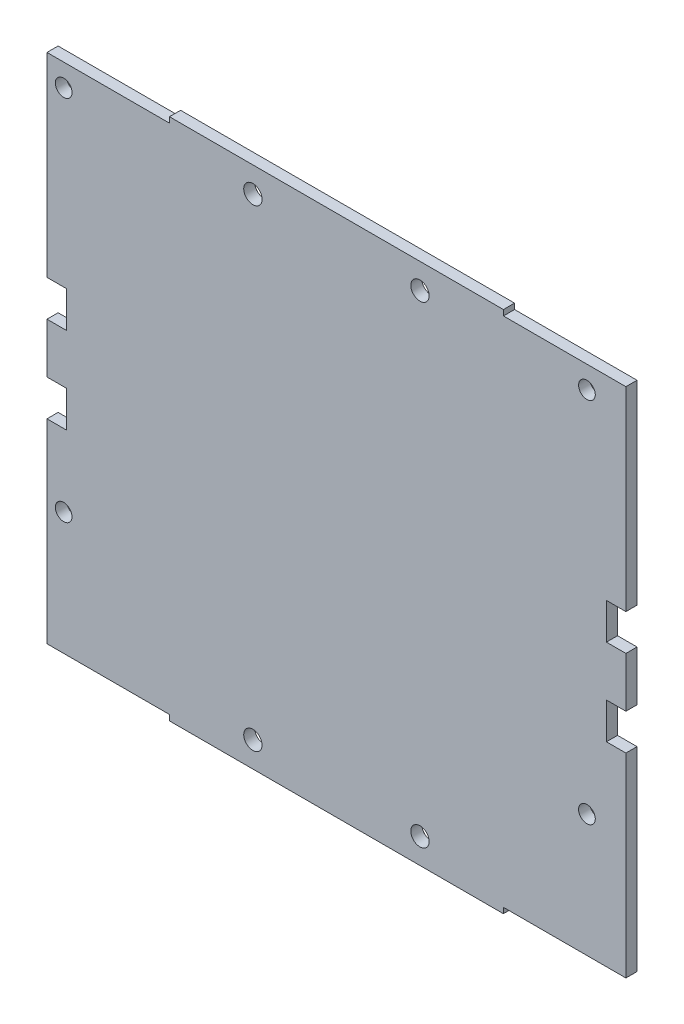
SolidWorks part; units mm, degrees
ref_plane "Front Plane" through (0, 0, 0) normal (0, 0, 1) x (1, 0, 0)
ref_plane "Top Plane" through (0, 0, 0) normal (0, 1, 0) x (1, 0, 0)
ref_plane "Right Plane" through (0, 0, 0) normal (1, 0, 0) x (0, 0, -1)
sketch "Sketch1" plane through (0, 0, 0) normal (0, 0, 1) x (1, 0, 0)
  line L1 (-53, -47.5) -> (53, -47.5)
  line L2 (-53, -47.5) -> (-53, 47.5)
  line L3 (-53, 47.5) -> (53, 47.5)
  line L4 (53, -47.5) -> (53, 47.5)
  line L5 (-53, -47.5) -> (53, 47.5) construction
  line L6 (-53, 47.5) -> (53, -47.5) construction
  line L7 (10.9414, 37.5603) -> (18.9351, 37.5603) construction
  line L8 (10.9414, 37.5603) -> (10.9414, 47.5654) construction
  line L9 (10.9414, 47.5654) -> (18.9351, 47.5654) construction
  line L10 (18.9351, 37.5603) -> (18.9351, 47.5654) construction
  line L11 (10.9414, 37.5603) -> (18.9351, 47.5654) construction
  line L12 (10.9414, 47.5654) -> (18.9351, 37.5603) construction
  line L13 (-19.0649, 47.5415) -> (-11.0586, 47.5415) construction
  line L14 (-19.0649, 47.5415) -> (-19.0649, 37.5465) construction
  line L15 (-19.0649, 37.5465) -> (-11.0586, 37.5465) construction
  line L16 (-11.0586, 47.5415) -> (-11.0586, 37.5465) construction
  line L17 (-19.0649, 47.5415) -> (-11.0586, 37.5465) construction
  line L18 (-19.0649, 37.5465) -> (-11.0586, 47.5415) construction
  point P0 (0, 0)
  point P6 (14.9383, 42.5629)
  point P7 (-15.0617, 42.544)
  dimension "D1" = 95
  dimension "D2" = 106
extrude "Boss-Extrude1" add sketch "Sketch1" along normal blind 2
hole_wizard "Tap Drill for M4x0.7 Tap1" positions "Sketch2" profile "Sketch3" hole size "M4x0.7" standard "ANSI Metric"
sketch "Sketch2" plane through (0, 0, 0) normal (0, 0, -1) x (-1, 0, 0)
  line L1 (-1000, 0) -> (49000, 0) construction
  line L2 (0, -1000) -> (0, 49000) construction
  line L3 (-53, -47.5) -> (-53, 47.5) construction
  line L4 (53, -47.5) -> (-53, -47.5) construction
  line L5 (-53, -47.5) -> (-53, 47.5) construction
  line L6 (53, -47.5) -> (-53, -47.5) construction
  line L8 (-53, -39.5) -> (-45, -39.5)
  line L9 (-53, -39.5) -> (-53, -47.5)
  line L10 (-53, -47.5) -> (-45, -47.5)
  line L11 (-45, -39.5) -> (-45, -47.5)
  line L12 (-53, -39.5) -> (-45, -47.5) construction
  line L13 (-53, -47.5) -> (-45, -39.5) construction
  point P20 (-49, -43.5)
  point P67 (49, -43.5)
  point P70 (-49, 43.5)
  point P72 (49, 43.5)
  dimension "D1" = 8
  dimension "D2" = 8
sketch "Sketch3" plane through (-49, 43.5, 0) normal (1, 0, 0) x (0, 1, 0)
  line L0 (0, 0) -> (0, 10.9914)
  line L1 (0, 10.9914) -> (1.65, 10)
  line L2 (1.65, 10) -> (1.65, 0.025)
  line L3 (1.65, 0.025) -> (1.675, 0)
  line L5 (1.675, 0) -> (0, 0)
  line L6 (-1.65, 0.025) -> (-1.675, 0) construction
  line L10 (0, 10.9914) -> (-1.65, 10) construction
  line L11 (0, -6.35) -> (0, 107.95) construction
  dimension "Hole Dia." = 3.3
  dimension "Hole Depth" = 10
  dimension "Near C'Sink Dia." = 3.35
  dimension "Near C'Sink Angle" = 90
  dimension "Drill Angle" = 118
sketch "Sketch4" plane through (0, 0, 0) normal (0, 0, -1) x (-1, 0, 0)
  line L0 (53, 47.5) -> (53, -47.5) construction
  line L1 (-52, 47) -> (52, 47)
  line L2 (-52, 47) -> (-52, -47)
  line L3 (-52, -47) -> (52, -47)
  line L4 (52, 47) -> (52, -47)
  line L5 (-52, 47) -> (52, -47) construction
  line L6 (-52, -47) -> (52, 47) construction
  line L7 (53, -47.5) -> (-53, -47.5) construction
  line L8 (-53, 47.5) -> (53, 47.5) construction
  line L9 (-64.139, -55.2308) -> (64.139, -55.2308)
  line L10 (-64.139, -55.2308) -> (-64.139, 55.2308)
  line L11 (-64.139, 55.2308) -> (64.139, 55.2308)
  line L12 (64.139, -55.2308) -> (64.139, 55.2308)
  line L13 (-64.139, -55.2308) -> (64.139, 55.2308) construction
  line L14 (-64.139, 55.2308) -> (64.139, -55.2308) construction
  point P0 (0, 0)
  point P9 (0, 0)
  dimension "D1" = 1
  dimension "D2" = 104
  dimension "D3" = 0.5
  dimension "D4" = 0.5
extrude "Cut-Extrude1" cut sketch "Sketch4" against normal blind 10
sketch "Sketch6" plane through (0, 0, 0) normal (0, 0, -1) x (-1, 0, 0)
  line L0 (-52, 47) -> (-52, -47) construction
  line L1 (-52, 47) -> (-52, -47) construction
  line L2 (52, -47) -> (52, 47) construction
  line L3 (52, -47) -> (52, 47) construction
  line L4 (-1000, 0) -> (49000, 0) construction
  line L5 (52, 47) -> (-52, 47) construction
  line L6 (-52, -4.5) -> (-48.5, -4.5)
  line L7 (-52, -4.5) -> (-52, -11)
  line L8 (-52, -11) -> (-48.5, -11)
  line L9 (-48.5, -4.5) -> (-48.5, -11)
  line L10 (-52, -47) -> (52, -47) construction
  line L11 (52, 47) -> (-52, 47) construction
  line L12 (-52, -47) -> (52, -47) construction
  line L13 (-52, 11) -> (-48.5, 11)
  line L14 (-48.5, 4.5) -> (-48.5, 11)
  line L15 (-52, 4.5) -> (-48.5, 4.5)
  line L16 (-52, 4.5) -> (-52, 11)
  line L17 (0, -1000) -> (0, 49000) construction
  line L18 (48.5, -4.5) -> (48.5, -11)
  line L19 (52, -11) -> (48.5, -11)
  line L20 (52, -4.5) -> (52, -11)
  line L21 (52, -4.5) -> (48.5, -4.5)
  line L22 (52, 4.5) -> (52, 11)
  line L23 (52, 4.5) -> (48.5, 4.5)
  line L24 (48.5, 4.5) -> (48.5, 11)
  line L25 (52, 11) -> (48.5, 11)
  line L26 (145.0049, -47.9405) -> (-131.9951, -47.7664) construction
  line L27 (-30, -46) -> (-52.4797, -46)
  line L28 (-30, -46) -> (-30, -47.8164)
  line L29 (-30, -47.8164) -> (-52.4797, -47.8164)
  line L30 (-52.4797, -46) -> (-52.4797, -47.8164)
  line L31 (52.4797, -46) -> (52.4797, -47.8164)
  line L32 (30, -47.8164) -> (52.4797, -47.8164)
  line L33 (30, -46) -> (30, -47.8164)
  line L34 (30, -46) -> (52.4797, -46)
  line L35 (-30, 46) -> (-30, 47.8164)
  line L36 (-30, 47.8164) -> (-52.4797, 47.8164)
  line L37 (-52.4797, 46) -> (-52.4797, 47.8164)
  line L38 (-30, 46) -> (-52.4797, 46)
  line L39 (30, 47.8164) -> (52.4797, 47.8164)
  line L40 (52.4797, 46) -> (52.4797, 47.8164)
  line L41 (30, 46) -> (30, 47.8164)
  line L42 (30, 46) -> (52.4797, 46)
  dimension "D1" = 3.5
  dimension "D2" = 36
  dimension "D3" = 6.5
  dimension "D4" = 1
extrude "Cut-Extrude2" cut sketch "Sketch6" against normal blind 5
sketch "Sketch8" plane through (0, 0, 0) normal (0, 0, -1) x (-1, 0, 0)
  line L0 (30, 47) -> (-30, 47) construction
  line L1 (-48, 47) -> (52, 47) construction
  line L3 (-48, -27) -> (52, -27) construction
  line L4 (52, 47) -> (52, -27) construction
  line L5 (30, 47) -> (-30, 47) construction
  line L6 (52, 11) -> (52, 46) construction
  line L7 (52, 11) -> (52, 46) construction
  line L8 (-52, 46) -> (-52, 11) construction
  line L9 (-52, 46) -> (-52, 11) construction
  line L10 (2, -1000.1713) -> (2, 48999.8287) construction
  line L11 (-1069.6143, 9) -> (48930.3857, 9) construction
  line L13 (-42, 47) -> (-34, 47) construction
  line L17 (-1000, 0) -> (49000, 0) construction
  line L18 (0, -1000) -> (0, 49000) construction
  line L21 (-52, 46) -> (-30, 46) construction
  line L22 (-973.363, 45) -> (49026.637, 45) construction
  line L23 (-52, 46) -> (-30, 46) construction
  circle A0 centre (-45, 42) radius 1.5
  circle A1 centre (-45, -24) radius 1.5
  circle A2 centre (49, 42) radius 1.5
  circle A3 centre (49, -24) radius 1.5
  point P10 (-45, 42)
  dimension "D5" = 36
  dimension "D4" = 72
  dimension "D1" = 3
  dimension "D2" = 100
  dimension "D3" = 5
  dimension "D6" = 50
extrude "Cut-Extrude3" cut sketch "Sketch8" against normal blind 5
sketch "Sketch10" plane through (0, 0, 0) normal (0, 0, -1) x (-1, 0, 0)
  line L0 (0, -1000) -> (0, 49000) construction
  line L1 (-1000, 0) -> (49000, 0) construction
  line L2 (-52, 46) -> (-30, 46) construction
  line L4 (-52, 46) -> (-30, 46) construction
  line L6 (19.0114, -37.4585) -> (19.0051, -47.4585) construction
  line L7 (11.0051, -47.4535) -> (11.0114, -37.4535) construction
  line L8 (19.0114, -37.4585) -> (19.0051, -47.4585) construction
  line L9 (11.0051, -47.4535) -> (11.0114, -37.4535) construction
  line L10 (11.0051, -47.4535) -> (19.0051, -47.4585) construction
  line L11 (11.0114, -37.4535) -> (19.0114, -37.4585) construction
  line L12 (11.0083, -42.4535) -> (19.0083, -42.4585) construction
  line L13 (15.0114, -37.456) -> (15.0051, -47.456) construction
  point P12 (15.0083, -42.456)
  point P19 (15.0083, 42.456)
  point P31 (-15.0083, -42.456)
  point P32 (-15.0083, 42.456)
hole_wizard "Tap Drill for M4x0.7 Tap2" positions "Sketch11" profile "Sketch12" hole size "M4x0.7" standard "ANSI Metric"
sketch "Sketch11" plane through (0, 0, 0) normal (0, 0, -1) x (-1, 0, 0)
  point P29 (-15.0083, 42.456)
  point P32 (-15.0083, -42.456)
  point P35 (15.0083, -42.456)
  point P38 (15.0083, 42.456)
sketch "Sketch12" plane through (15.0083, 42.456, 0) normal (1, 0, 0) x (0, 1, 0)
  line L0 (0, 0) -> (0, 10.9914)
  line L1 (0, 10.9914) -> (1.65, 10)
  line L2 (1.65, 10) -> (1.65, 0.025)
  line L3 (1.65, 0.025) -> (1.675, 0)
  line L5 (1.675, 0) -> (0, 0)
  line L6 (-1.65, 0.025) -> (-1.675, 0) construction
  line L10 (0, 10.9914) -> (-1.65, 10) construction
  line L11 (0, -6.35) -> (0, 107.95) construction
  dimension "Hole Dia." = 3.3
  dimension "Hole Depth" = 10
  dimension "Near C'Sink Dia." = 3.35
  dimension "Near C'Sink Angle" = 90
  dimension "Drill Angle" = 118
